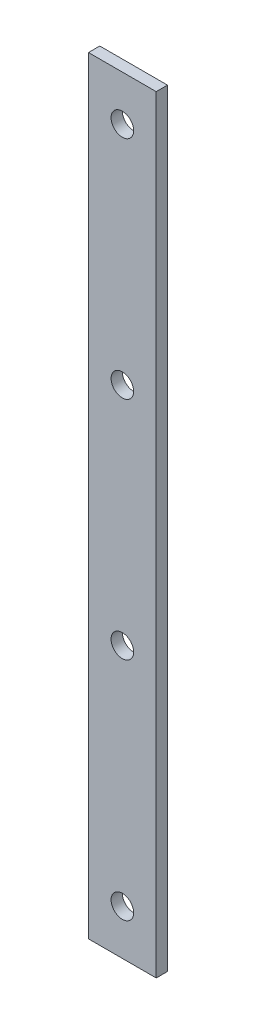
SolidWorks part; units mm, degrees
ref_plane "Front Plane" through (0, 0, 0) normal (0, 0, 1) x (1, 0, 0)
ref_plane "Top Plane" through (0, 0, 0) normal (0, 1, 0) x (1, 0, 0)
ref_plane "Right Plane" through (0, 0, 0) normal (1, 0, 0) x (0, 0, -1)
sketch "Sketch1" plane through (0, 0, 0) normal (0, 0, 1) x (1, 0, 0)
  line L0 (55, 0) -> (-55, 0) construction
  line L1 (-15, -170) -> (15, -170)
  line L2 (-15, -170) -> (-15, 170)
  line L3 (-15, 170) -> (15, 170)
  line L4 (15, -170) -> (15, 170)
  line L5 (-15, -170) -> (15, 170) construction
  line L6 (-15, 170) -> (15, -170) construction
  circle A0 centre (0, -50) radius 5
  circle A1 centre (0, -150) radius 5
  circle A2 centre (0, 50) radius 5
  circle A3 centre (0, 150) radius 5
  point P0 (0, 0)
  point P16 (0, 0)
  point P17 (0, -170)
  dimension "D3" = 50
  dimension "D5" = 10
  dimension "D1" = 340
  dimension "D2" = 30
  dimension "D4" = 100
extrude "Boss-Extrude1" add sketch "Sketch1" along normal blind 5
